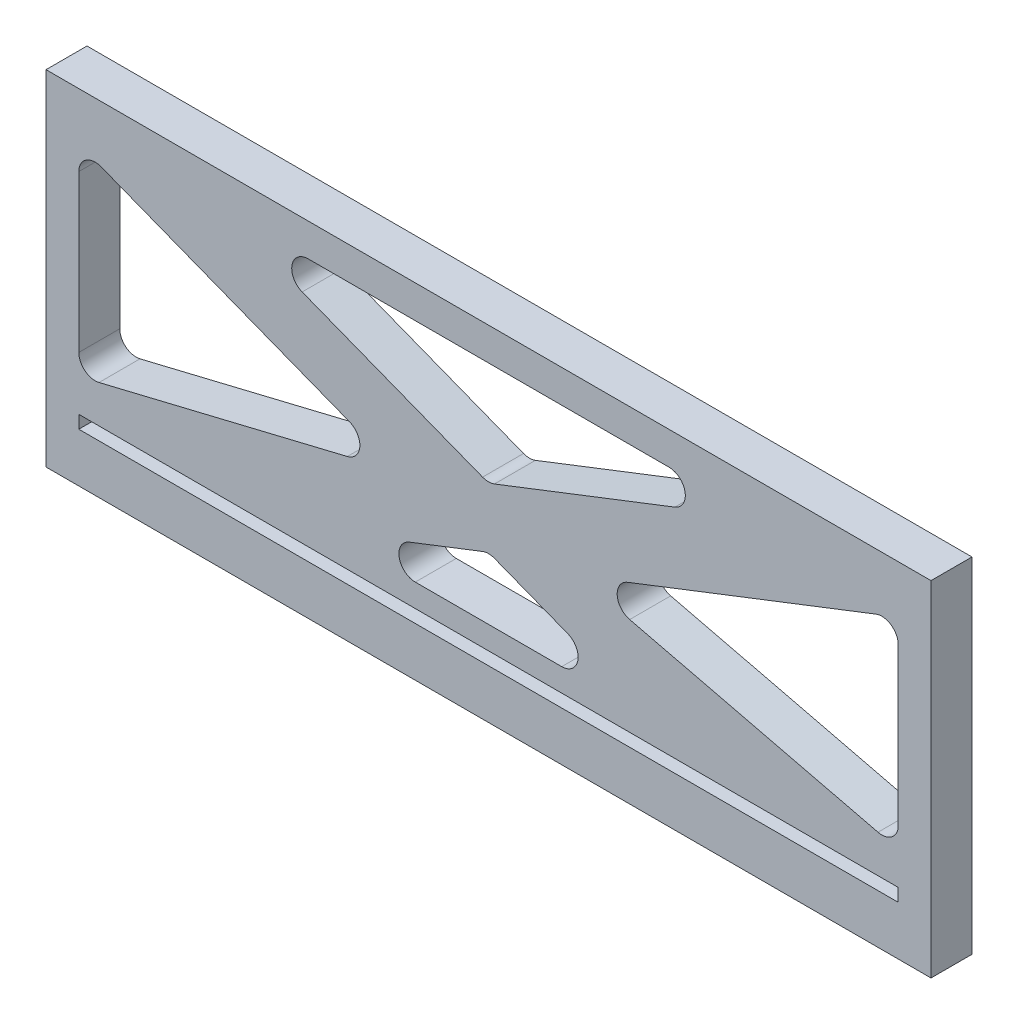
SolidWorks part; units mm, degrees
ref_plane "Front Plane" through (0, 0, 0) normal (0, 0, 1) x (1, 0, 0)
ref_plane "Top Plane" through (0, 0, 0) normal (0, 1, 0) x (1, 0, 0)
ref_plane "Right Plane" through (0, 0, 0) normal (1, 0, 0) x (0, 0, -1)
sketch "Sketch1" plane through (0, 0, 0) normal (0, 0, 1) x (1, 0, 0)
  line L0 (-20.7506, 10.795) -> (0, 2.7253)
  line L1 (-34.29, -13.335) -> (34.29, -13.335)
  line L2 (-34.29, -13.335) -> (-34.29, 13.335)
  line L3 (-34.29, 13.335) -> (34.29, 13.335)
  line L4 (34.29, -13.335) -> (34.29, 13.335)
  line L5 (-34.29, -13.335) -> (34.29, 13.335) construction
  line L6 (-34.29, 13.335) -> (34.29, -13.335) construction
  line L7 (-31.75, -9.525) -> (31.75, -9.525)
  line L8 (-31.75, -9.525) -> (-31.75, -8.525)
  line L9 (-31.75, -8.525) -> (31.75, -8.525)
  line L10 (31.75, -9.525) -> (31.75, -8.525)
  line L11 (-31.75, -9.525) -> (31.75, -8.525) construction
  line L12 (-31.75, -8.525) -> (31.75, -9.525) construction
  line L13 (0, 2.7253) -> (20.7506, 10.795)
  line L14 (20.7506, 10.795) -> (-20.7506, 10.795)
  line L15 (0, 0) -> (0, 2.7253) construction
  line L16 (-10.3753, 6.7602) -> (-11.2959, 4.3929) construction
  line L17 (10.3753, 6.7602) -> (11.2959, 4.3929) construction
  line L18 (0, 10.795) -> (0, 13.335) construction
  line L19 (-31.75, 9.6219) -> (-31.75, -5.985)
  line L20 (-31.75, -5.985) -> (-7.0079, 0)
  line L21 (-7.0079, 0) -> (-31.75, 9.6219)
  line L22 (7.0079, 0) -> (-7.0079, 0) construction
  line L23 (-19.379, 4.811) -> (-18.4584, 7.1782) construction
  line L24 (7.0079, 0) -> (31.75, 9.6219)
  line L25 (31.75, 9.6219) -> (31.75, -5.985)
  line L26 (31.75, -5.985) -> (7.0079, 0)
  line L27 (0, -1.9077) -> (-12.4439, -6.747)
  line L28 (-12.4439, -6.747) -> (12.4439, -6.747)
  line L29 (12.4439, -6.747) -> (0, -1.9077)
  line L30 (0, -1.9077) -> (0, 0) construction
  line L31 (-6.2219, -4.3274) -> (-6.8664, -2.6703) construction
  line L32 (6.2219, -4.3274) -> (6.8664, -2.6703) construction
  line L33 (0, -6.747) -> (0, -8.525) construction
  point P0 (0, 0)
  point P6 (0, -9.025)
  point P27 (0, 0)
  dimension "D1" = 3.81
  dimension "D2" = 2.54
  dimension "D3" = 68.58
  dimension "D4" = 26.67
  dimension "D5" = 1
  dimension "D6" = 2.54
  dimension "D7" = 2.54
  dimension "D8" = 2.54
  dimension "D9" = 1.778
extrude "Boss-Extrude1" add sketch "Sketch1" along normal blind 3.175
fillet "Fillet1" radius 1.27 12 edges at (31.75, 9.6219, 1.5875) (31.75, -5.985, 1.5875) (7.0079, 0, 1.5875) (20.7506, 10.795, 1.5875) (-20.7506, 10.795, 1.5875) (0, 2.7253, 1.5875) (-7.0079, 0, 1.5875) (-31.75, 9.6219, 1.5875) (-31.75, -5.985, 1.5875) (12.4439, -6.747, 1.5875) (0, -1.9077, 1.5875) (-12.4439, -6.747, 1.5875)
